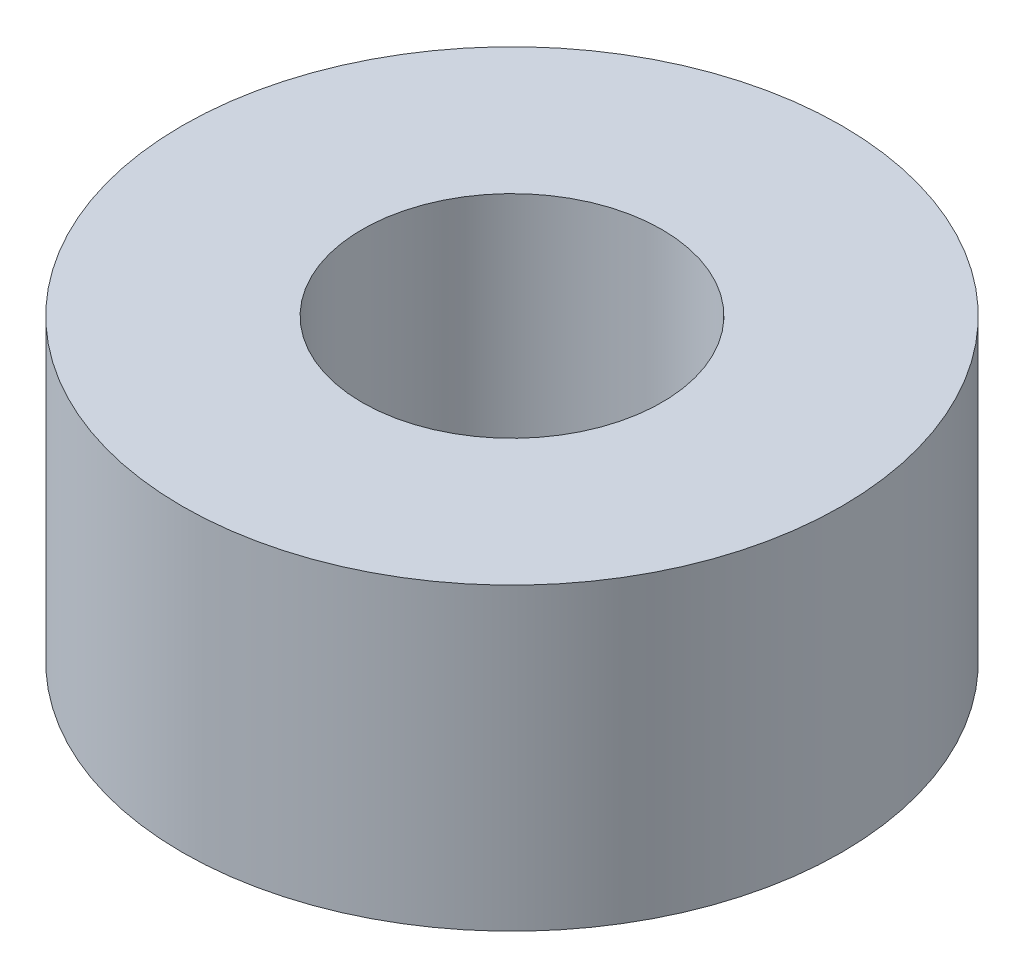
SolidWorks part; units mm, degrees
ref_plane "Front Plane" through (0, 0, 0) normal (0, 0, 1) x (1, 0, 0)
ref_plane "Top Plane" through (0, 0, 0) normal (0, 1, 0) x (1, 0, 0)
ref_plane "Right Plane" through (0, 0, 0) normal (1, 0, 0) x (0, 0, -1)
sketch "Sketch1" plane through (0, 0, 0) normal (0, 1, 0) x (1, 0, 0)
  circle A0 centre (0, 0) radius 2.5
  circle A1 centre (0, 0) radius 5.5
  dimension "D1" = 5
  dimension "D2" = 11
extrude "Boss-Extrude1" add sketch "Sketch1" along normal blind 5
equation "\"a\"= 1"
equation "\"b\"= 1"
equation "\"c\"= 1"
equation "\"d\"= 1"
equation "\"e\"= 1"
equation "\"x\"= 1"
equation "\"y\"= 1"
equation "\"z\"= 1"
